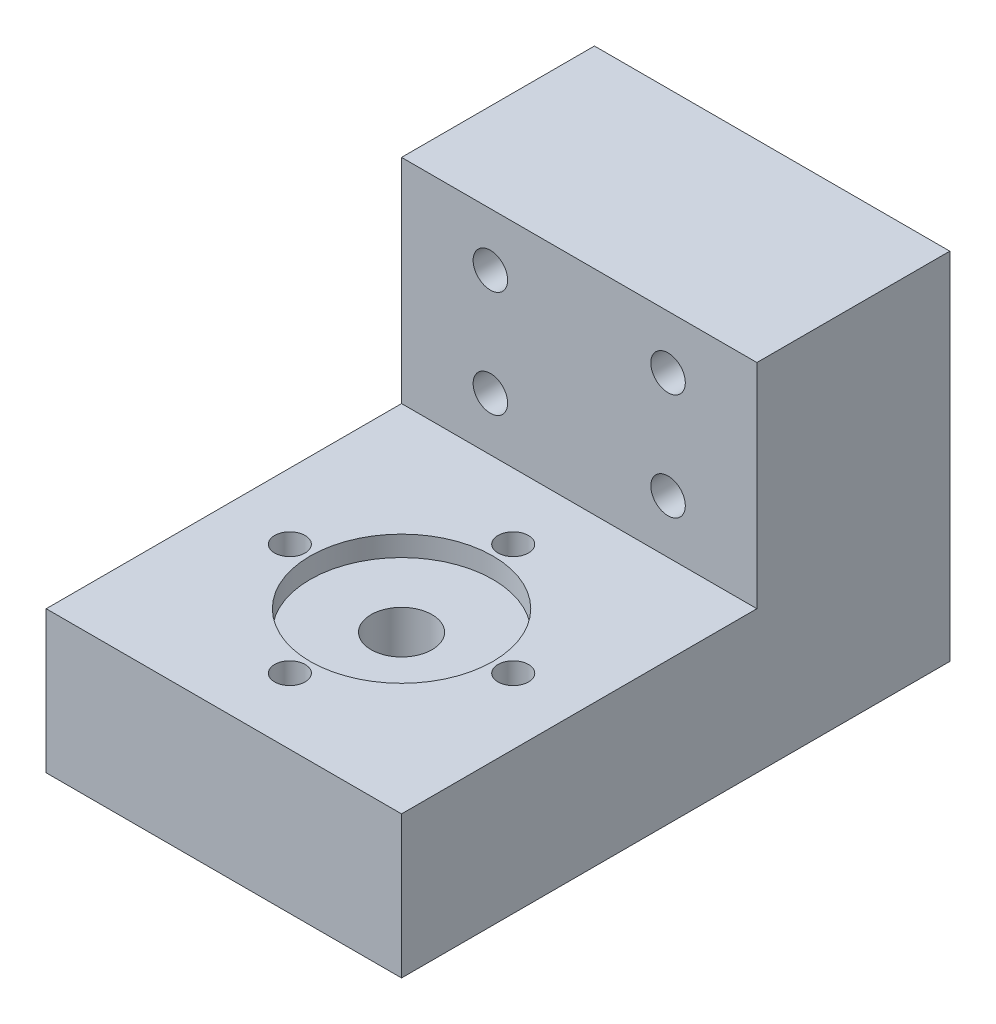
SolidWorks part; units mm, degrees
material "ABS"
ref_plane "Front Plane" through (0, 0, 0) normal (0, 0, 1) x (1, 0, 0)
ref_plane "Top Plane" through (0, 0, 0) normal (0, 1, 0) x (1, 0, 0)
ref_plane "Right Plane" through (0, 0, 0) normal (1, 0, 0) x (0, 0, -1)
sketch "Sketch1" plane through (0, 0, 0) normal (0, 0, 1) x (1, 0, 0)
  line L1 (0, 0) -> (35, 0)
  line L2 (0, 0) -> (0, 35)
  line L3 (0, 35) -> (35, 35)
  line L4 (35, 0) -> (35, 35)
  dimension "D1" = 35
  dimension "D2" = 35
extrude "Boss-Extrude1" add sketch "Sketch1" along normal blind 19 contours L3 L4 L1 L2
sketch "Sketch2" plane through (0, 0, 19) normal (0, 0, 1) x (1, 0, 0)
  line L0 (35, 0) -> (35, 35) construction
  line L1 (0, 0) -> (35, 0)
  line L2 (0, 0) -> (0, 14)
  line L3 (0, 14) -> (35, 14)
  line L4 (35, 0) -> (35, 14)
  dimension "D1" = 14
extrude "Boss-Extrude2" add sketch "Sketch2" along normal blind 35
sketch "Sketch3" plane through (0, 14, 0) normal (0, 1, 0) x (1, 0, 0)
  circle A0 centre (17.5, -36.5) radius 3
  dimension "D1" = 6
extrude "Cut-Extrude1" cut sketch "Sketch3" against normal through all
sketch "Sketch4" plane through (0, 14, 0) normal (0, 1, 0) x (1, 0, 0)
  circle A0 centre (17.5, -36.5) radius 9
  dimension "D1" = 18
extrude "Cut-Extrude2" cut sketch "Sketch4" against normal blind 2
sketch "Sketch6" plane through (0, 14, 0) normal (0, 1, 0) x (1, 0, 0)
  line L0 (17.5, -36.5) -> (17.5, -17.8947) construction
  line L1 (17.5, -36.5) -> (50017.5, -36.5) construction
  circle A0 centre (17.5, -36.5) radius 11 construction
  circle A1 centre (6.5, -36.5) radius 1.5
  circle A2 centre (17.5, -25.5) radius 1.5
  circle A3 centre (28.5, -36.5) radius 1.5
  circle A4 centre (17.5, -47.5) radius 1.5
  dimension "D1" = 22
  dimension "D2" = 3
  dimension "D3" = 3
  dimension "D4" = 3
  dimension "D5" = 3
extrude "Cut-Extrude3" cut sketch "Sketch6" against normal through all
sketch "Sketch7" plane through (0, 0, 19) normal (0, 0, 1) x (1, 0, 0)
  circle A0 centre (8.75, 29.75) radius 1.7
  circle A1 centre (26.25, 29.75) radius 1.7
  circle A2 centre (8.75, 19.25) radius 1.7
  circle A3 centre (26.25, 19.25) radius 1.7
  dimension "D1" = 3.4
  dimension "D2" = 3.4
  dimension "D3" = 3.4
  dimension "D4" = 3.4
  dimension "D5" = 5.25
  dimension "D6" = 5.25
  dimension "D7" = 5.25
  dimension "D8" = 5.25
  dimension "D9" = 8.75
  dimension "D10" = 8.75
  dimension "D11" = 8.75
  dimension "D12" = 8.75
extrude "Cut-Extrude4" cut sketch "Sketch7" against normal through all
equation "\"D3@Sketch6\"=\"D2@Sketch6\""
equation "\"D4@Sketch6\"=\"D2@Sketch6\""
equation "\"D5@Sketch6\"=\"D2@Sketch6\""
equation "\"D2@Sketch7\"=\"D1@Sketch7\""
equation "\"D3@Sketch7\"=\"D1@Sketch7\""
equation "\"D4@Sketch7\"=\"D1@Sketch7\""
equation "\"D7@Sketch7\"=\"D6@Sketch7\""
equation "\"D8@Sketch7\"=\"D5@Sketch7\""
equation "\"D10@Sketch7\"=\"D9@Sketch7\""
equation "\"D11@Sketch7\"=\"D9@Sketch7\""
equation "\"D12@Sketch7\"=\"D9@Sketch7\""
